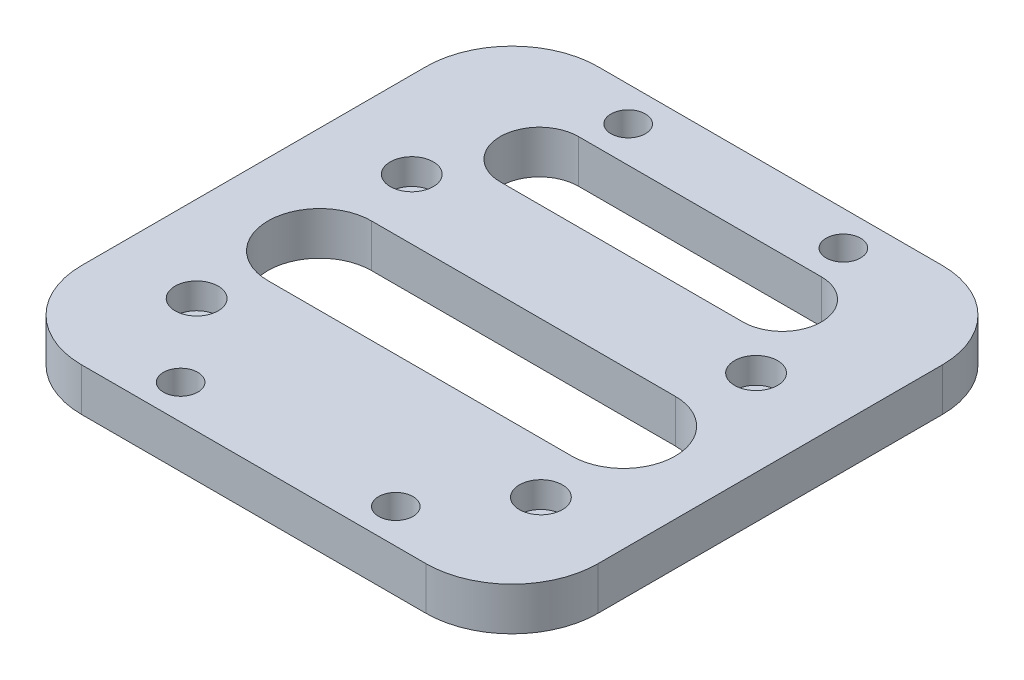
SolidWorks part; units mm, degrees
ref_plane "Plan de face" through (0, 0, 0) normal (0, 0, 1) x (1, 0, 0)
ref_plane "Plan de dessus" through (0, 0, 0) normal (0, 1, 0) x (1, 0, 0)
ref_plane "Plan de droite" through (0, 0, 0) normal (1, 0, 0) x (0, 0, -1)
sketch "Esquisse1" plane through (0, 0, 0) normal (0, 1, 0) x (1, 0, 0)
  line L1 (0, 0) -> (60, 0)
  line L2 (0, 0) -> (0, 60)
  line L3 (0, 60) -> (60, 60)
  line L4 (60, 0) -> (60, 60)
  dimension "D1" = 60
  dimension "D2" = 60
extrude "Boss.-Extru.1" add sketch "Esquisse1" along normal blind 5
sketch "Esquisse2" plane through (0, 5, 0) normal (0, 1, 0) x (1, 0, 0)
  line L1 (17.5, 56) -> (17.5, 4) construction
  line L2 (17.5, 4) -> (42.5, 4) construction
  line L3 (0, 60) -> (0, 0) construction
  line L4 (0, 0) -> (60, 0) construction
  line L5 (10, 38.3585) -> (10, 60.8585) construction
  line L6 (10, 13.3585) -> (10, 0.8585) construction
  line L7 (60, 0) -> (60, 60) construction
  circle A0 centre (17.5, 56) radius 2
  circle A1 centre (17.5, 4) radius 2
  circle A2 centre (42.5, 4) radius 2
  circle A3 centre (42.5, 56) radius 2
  circle A4 centre (10, 38.3585) radius 1.3
  circle A5 centre (10, 13.3585) radius 1.3
  circle A6 centre (50, 13.3585) radius 1.3
  circle A7 centre (50, 38.3585) radius 1.3
  point P8 (17.5, 30)
  point P11 (0, 30)
  point P12 (30, 4)
  point P15 (30, 0)
  point P24 (25.3329, 13.8213)
  point P28 (25, 46.1768)
  point P30 (25, 38.3585)
  point P31 (0, 0)
  point P32 (0, 0)
  point P33 (0, 0)
  point P34 (0, 0)
  dimension "D5" = 4
  dimension "D6" = 2.6
  dimension "D1" = 52
  dimension "D3" = 25
  dimension "D7" = 25
  dimension "D8" = 22.5
  dimension "D9" = 12.5
  dimension "D10" = 10
  dimension "D11" = 10
extrude "Enlèv. mat.-Extru.1" cut sketch "Esquisse2" against normal through all
sketch "Esquisse4" plane through (0, 5, 0) normal (0, 1, 0) x (1, 0, 0)
  circle A0 centre (10, 38.3585) radius 2.5
  circle A1 centre (10, 13.3585) radius 2.5
  circle A2 centre (50, 13.3585) radius 2.5
  circle A3 centre (50, 38.3585) radius 2.5
  dimension "D1" = 5
extrude "Enlèv. mat.-Extru.2" cut sketch "Esquisse4" against normal blind 3
fillet "Congé1" radius 10 4 edges at (60, 2.5, 0) (60, 2.5, -60) (0, 2.5, 0) (0, 2.5, -60)
sketch "Esquisse6" plane through (0, 5, 0) normal (0, 1, 0) x (1, 0, 0)
  line L0 (15.8936, 47.2818) -> (44.1064, 47.2818) construction
  line L1 (15.8936, 51.834) -> (44.1064, 51.834)
  line L2 (15.8936, 42.7295) -> (44.1064, 42.7295)
  line L3 (50, 60) -> (10, 60) construction
  line L6 (12.3529, 25.3072) -> (47.6471, 25.3072) construction
  line L7 (12.3529, 31.3207) -> (47.6471, 31.3207)
  line L8 (12.3529, 19.2937) -> (47.6471, 19.2937)
  arc A0 (15.8936, 51.834) -> (15.8936, 42.7295) centre (15.8936, 47.2818) ccw
  arc A1 (44.1064, 42.7295) -> (44.1064, 51.834) centre (44.1064, 47.2818) ccw
  arc A4 (12.3529, 31.3207) -> (12.3529, 19.2937) centre (12.3529, 25.3072) ccw
  arc A5 (47.6471, 19.2937) -> (47.6471, 31.3207) centre (47.6471, 25.3072) ccw
  point P2 (30, 47.2818)
  point P7 (0, 0)
  point P10 (30, 60)
  point P11 (43.7692, 19.2937)
  point P12 (44.7808, 41.7741)
  point P16 (30, 25.3072)
extrude "Enlèv. mat.-Extru.4" cut sketch "Esquisse6" against normal through all
